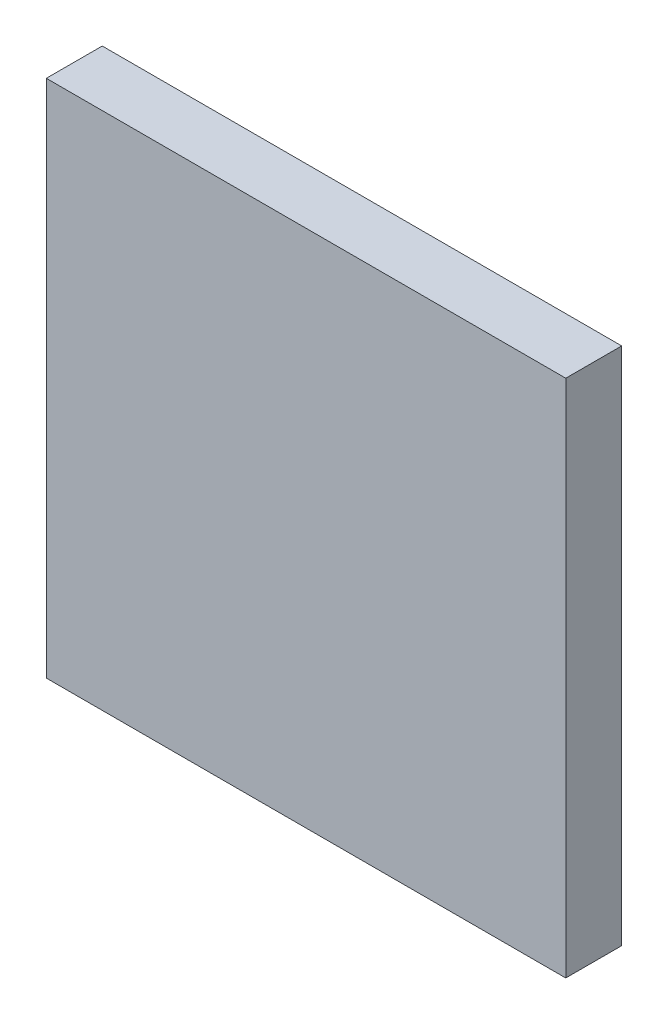
SolidWorks part; units mm, degrees
ref_plane "Front Plane" through (0, 0, 0) normal (0, 0, 1) x (1, 0, 0)
ref_plane "Top Plane" through (0, 0, 0) normal (0, 1, 0) x (1, 0, 0)
ref_plane "Right Plane" through (0, 0, 0) normal (1, 0, 0) x (0, 0, -1)
sketch "Sketch1" plane through (0, 0, 0) normal (0, 0, 1) x (1, 0, 0)
  line L1 (0, 0) -> (16.51, 0)
  line L2 (0, 0) -> (0, 16.51)
  line L3 (0, 16.51) -> (16.51, 16.51)
  line L4 (16.51, 0) -> (16.51, 16.51)
  dimension "D1" = 16.51
  dimension "D2" = 16.51
extrude "Boss-Extrude1" add sketch "Sketch1" along normal blind 1.778
